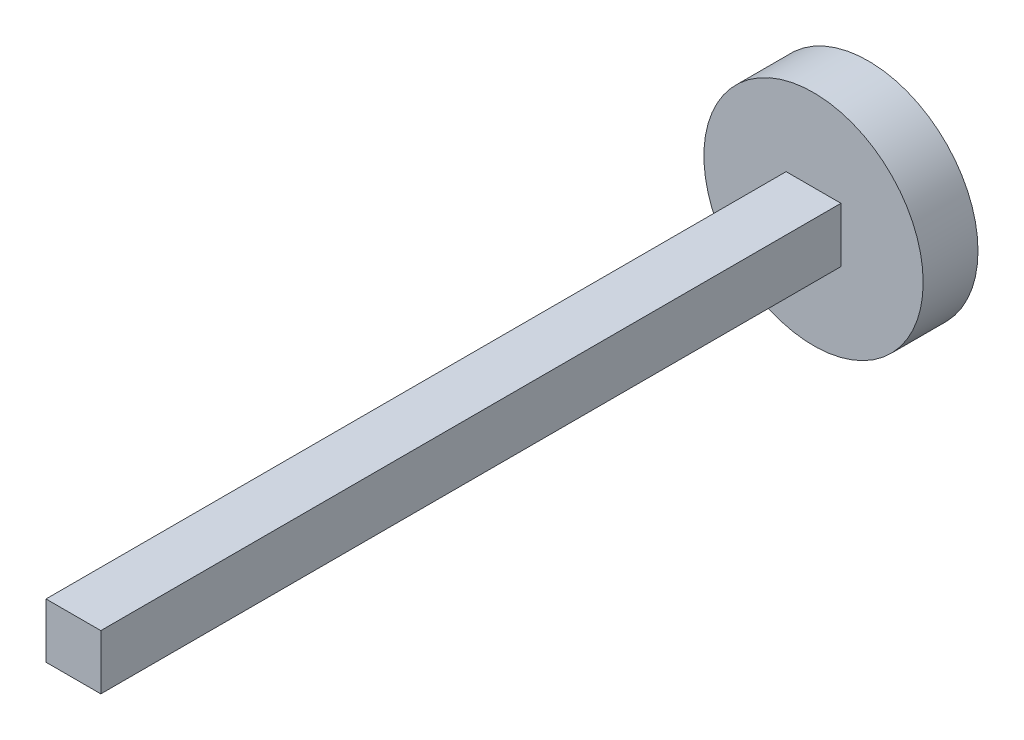
SolidWorks part; units mm, degrees
ref_plane "Front Plane" through (0, 0, 0) normal (0, 0, 1) x (1, 0, 0)
ref_plane "Top Plane" through (0, 0, 0) normal (0, 1, 0) x (1, 0, 0)
ref_plane "Right Plane" through (0, 0, 0) normal (1, 0, 0) x (0, 0, -1)
sketch "Sketch1" plane through (0, 0, 0) normal (0, 0, 1) x (1, 0, 0)
  circle A0 centre (0, 0) radius 40
  dimension "D1" = 80
extrude "Boss-Extrude1" add sketch "Sketch1" along normal blind 20
sketch "Sketch2" plane through (0, 0, 20) normal (0, 0, 1) x (1, 0, 0)
  line L1 (-10, -10) -> (10, -10)
  line L2 (-10, -10) -> (-10, 10)
  line L3 (-10, 10) -> (10, 10)
  line L4 (10, -10) -> (10, 10)
  line L5 (-10, -10) -> (10, 10) construction
  line L6 (-10, 10) -> (10, -10) construction
  point P0 (0, 0)
  dimension "D1" = 20
  dimension "D2" = 20
extrude "Boss-Extrude2" add sketch "Sketch2" along normal blind 270
